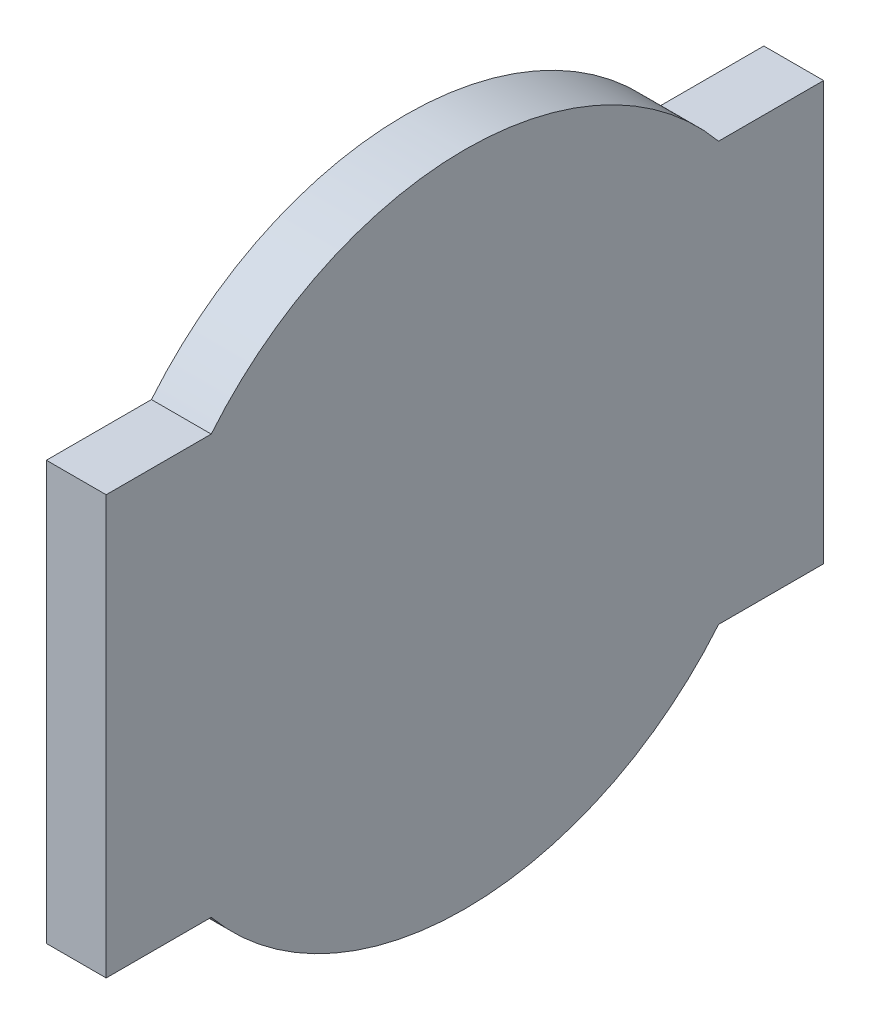
SolidWorks part; units mm, degrees
material "PE High Density"
ref_plane "Front Plane" through (0, 0, 0) normal (0, 0, 1) x (1, 0, 0)
ref_plane "Top Plane" through (0, 0, 0) normal (0, 1, 0) x (1, 0, 0)
ref_plane "Right Plane" through (0, 0, 0) normal (1, 0, 0) x (0, 0, -1)
sketch "Sketch1" plane through (0, 0, 0) normal (1, 0, 0) x (0, 0, -1)
  line L1 (-38.1, -22.225) -> (38.1, -22.225)
  line L2 (-38.1, -22.225) -> (-38.1, 22.225)
  line L3 (-38.1, 22.225) -> (38.1, 22.225)
  line L4 (38.1, -22.225) -> (38.1, 22.225)
  line L5 (-38.1, -22.225) -> (38.1, 22.225) construction
  line L6 (-38.1, 22.225) -> (38.1, -22.225) construction
  circle A0 centre (0, 0) radius 34.925
  point P0 (0, 0)
  dimension "D3" = 69.85
  dimension "D1" = 44.45
  dimension "D2" = 76.2
extrude "Boss-Extrude1" add sketch "Sketch1" along normal blind 6.35 contours L3 A0 L1 | A0 L3 L2 L1 | L3 A0 | A0 L1 L4 L3 | L1 A0
